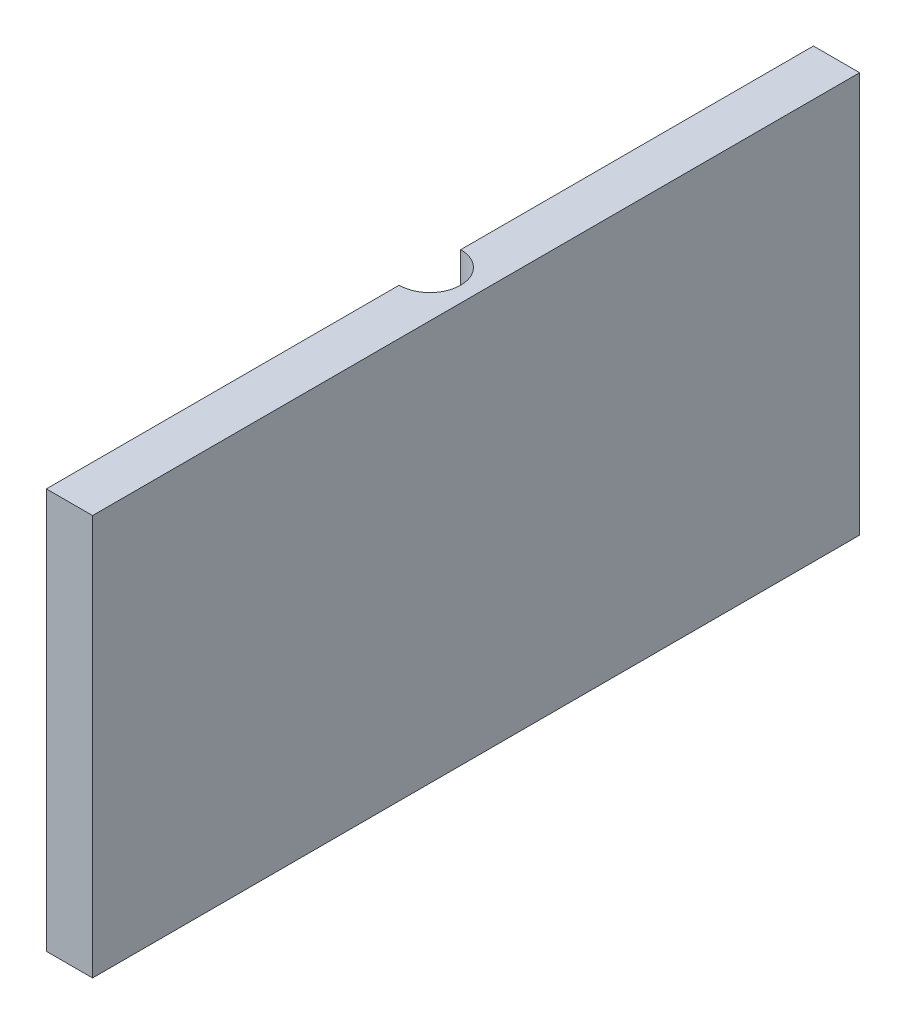
SolidWorks part; units mm, degrees
material "Klon"
ref_plane "Płaszczyzna przednia" through (0, 0, 0) normal (0, 0, 1) x (1, 0, 0)
ref_plane "Płaszczyzna górna" through (0, 0, 0) normal (0, 1, 0) x (1, 0, 0)
ref_plane "Płaszczyzna prawa" through (0, 0, 0) normal (1, 0, 0) x (0, 0, -1)
sketch "Szkic1" plane through (0, 0, 0) normal (0, 1, 0) x (1, 0, 0)
  line L1 (-7.5, -124.5) -> (7.5, -124.5)
  line L2 (-7.5, -124.5) -> (-7.5, 124.5)
  line L3 (-7.5, 124.5) -> (7.5, 124.5)
  line L4 (7.5, -124.5) -> (7.5, 124.5)
  line L5 (-7.5, -124.5) -> (7.5, 124.5) construction
  line L6 (-7.5, 124.5) -> (7.5, -124.5) construction
  point P0 (0, 0)
  dimension "D1" = 15
  dimension "D2" = 249
extrude "Dodanie-wyciągnięcie1" add sketch "Szkic1" along normal blind 130
sketch "Szkic2" plane through (0, 130, 0) normal (0, 1, 0) x (1, 0, 0)
  line L0 (-7.5, 124.5) -> (-7.5, -124.5) construction
  circle A0 centre (-7.5, 0) radius 10
extrude "Wytnij-wyciągnięcie1" cut sketch "Szkic2" against normal blind 50
